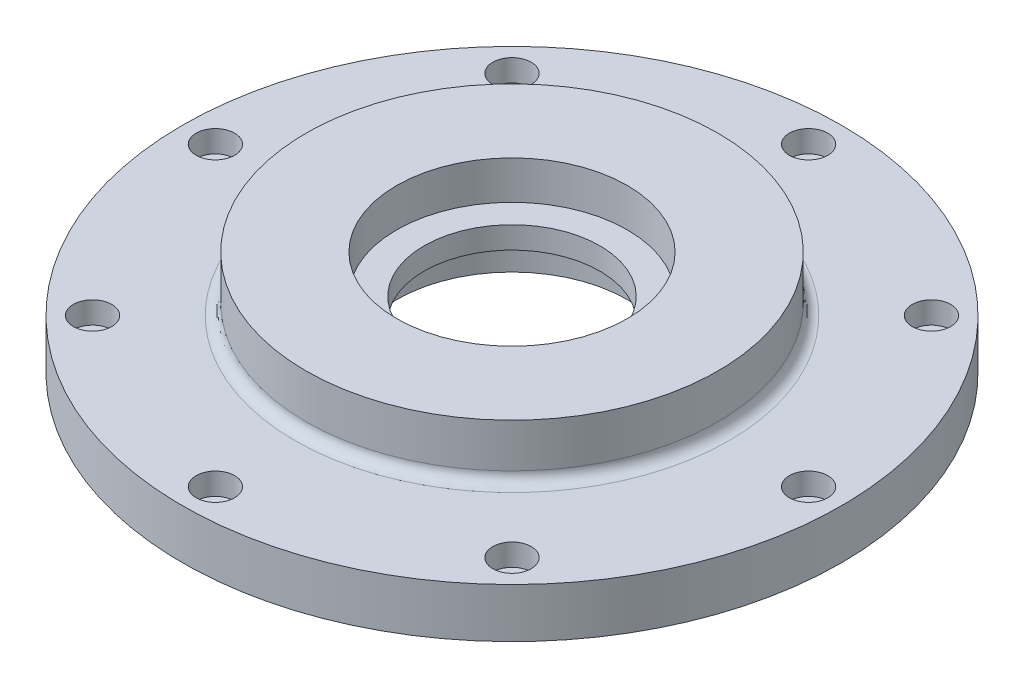
SolidWorks part; units mm, degrees
ref_plane "Front Plane" through (0, 0, 0) normal (0, 0, 1) x (1, 0, 0)
ref_plane "Top Plane" through (0, 0, 0) normal (0, 1, 0) x (1, 0, 0)
ref_plane "Right Plane" through (0, 0, 0) normal (1, 0, 0) x (0, 0, -1)
sketch "Sketch1" plane through (0, 0, 0) normal (0, 0, 1) x (1, 0, 0)
  line L0 (0, 11) -> (0, -37.6129) construction
  line L1 (-21, 11) -> (-60, 11)
  line L2 (-60, 11) -> (-60, -8)
  line L3 (-60, -8) -> (-21, -8)
  line L4 (-21, -8) -> (-21, 0)
  line L5 (-21, 0) -> (-16, 0)
  line L6 (-16, 0) -> (-16, 4)
  line L7 (-16, 4) -> (-21, 4)
  line L8 (-21, 4) -> (-21, 11)
  dimension "D1" = 21
  dimension "D2" = 21
  dimension "D3" = 16
  dimension "D4" = 60
  dimension "D5" = 19
  dimension "D6" = 8
  dimension "D7" = 7
revolve "Revolve1" add sketch "Sketch1" angle 360 about L0
sketch "Sketch3" plane through (0, 11, 0) normal (0, -1, 0) x (1, 0, 0)
  circle A0 centre (0, 0) radius 67.9645
  circle A1 centre (0, 0) radius 37.5
  dimension "D1" = 75
extrude "Cut-Extrude3" cut sketch "Sketch3" along normal blind 10
sketch "Sketch4" plane through (0, -8, 0) normal (0, -1, 0) x (1, 0, 0)
  circle A0 centre (0, 0) radius 35.5
  dimension "D1" = 71
extrude "Cut-Extrude4" cut sketch "Sketch4" against normal blind 1
sketch "Sketch6" plane through (0, 1, 0) normal (0, 1, 0) x (1, 0, 0)
  circle A0 centre (0, 54) radius 2
  circle A1 centre (38.1838, 38.1838) radius 2
  circle A2 centre (54, 0) radius 2
  circle A3 centre (38.1838, -38.1838) radius 2
  circle A4 centre (0, -54) radius 2
  circle A5 centre (-38.1838, -38.1838) radius 2
  circle A6 centre (-54, 0) radius 2
  circle A7 centre (-38.1838, 38.1838) radius 2
  point P18 (0, 0)
  dimension "D1" = 4
  dimension "D3" = 54
  dimension "D2" = 8
extrude "Cut-Extrude5" cut sketch "Sketch6" against normal blind 10
sketch "Sketch7" plane through (0, 1, 0) normal (0, 1, 0) x (1, 0, 0)
  circle A0 centre (0, 54) radius 3.5
  circle A1 centre (38.1838, 38.1838) radius 3.5
  circle A2 centre (54, 0) radius 3.5
  circle A3 centre (38.1838, -38.1838) radius 3.5
  circle A4 centre (0, -54) radius 3.5
  circle A5 centre (-38.1838, -38.1838) radius 3.5
  circle A6 centre (-54, 0) radius 3.5
  circle A7 centre (-38.1838, 38.1838) radius 3.5
  point P19 (0, 0)
  dimension "D1" = 7
  dimension "D2" = 8
extrude "Cut-Extrude6" cut sketch "Sketch7" against normal blind 4
fillet "Fillet1" radius 2 1 edges at (0, 1, -37.5)
